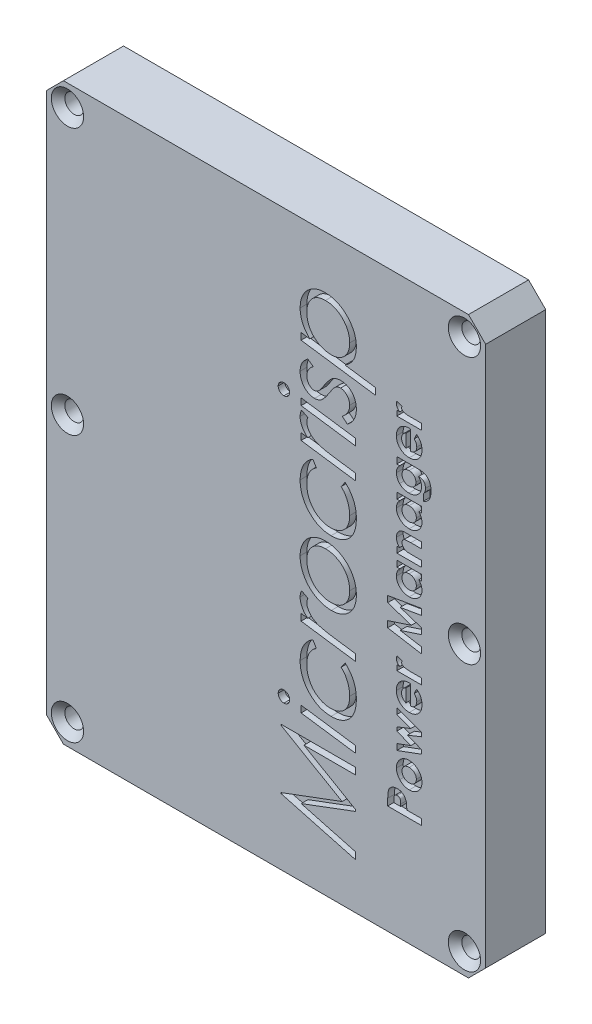
SolidWorks part; units mm, degrees
ref_plane "Front Plane" through (0, 0, 0) normal (0, 0, 1) x (1, 0, 0)
ref_plane "Top Plane" through (0, 0, 0) normal (0, 1, 0) x (1, 0, 0)
ref_plane "Right Plane" through (0, 0, 0) normal (1, 0, 0) x (0, 0, -1)
sketch "Sketch1" plane through (0, 0, 0) normal (0, 0, 1) x (1, 0, 0)
  line L0 (-27.5, 37.5) -> (27.5, 37.5) construction
  line L1 (27.5, 37.5) -> (27.5, -37.5) construction
  line L2 (27.5, -37.5) -> (-27.5, -37.5) construction
  line L3 (-27.5, -37.5) -> (-27.5, 37.5) construction
  line L4 (-27.5, 37.5) -> (27.5, 37.5)
  line L5 (27.5, 37.5) -> (27.5, -37.5)
  line L6 (27.5, -37.5) -> (-27.5, -37.5)
  line L7 (-27.5, -37.5) -> (-27.5, 37.5)
  line L8 (29.96, 42.5) -> (-29.96, 42.5)
  line L9 (-29.96, 42.5) -> (-32.5, 39.96)
  line L10 (-32.5, 39.96) -> (-32.5, -39.96)
  line L11 (-32.5, -39.96) -> (-29.96, -42.5)
  line L12 (-29.96, -42.5) -> (29.96, -42.5)
  line L13 (29.96, -42.5) -> (32.5, -39.96)
  line L14 (32.5, -39.96) -> (32.5, 39.96)
  line L15 (32.5, 39.96) -> (29.96, 42.5)
  line L16 (29.96, 42.5) -> (-29.96, 42.5)
  line L17 (-29.96, 42.5) -> (-32.5, 39.96)
  line L18 (-32.5, 39.96) -> (-32.5, -39.96)
  line L19 (-32.5, -39.96) -> (-29.96, -42.5)
  line L20 (-29.96, -42.5) -> (29.96, -42.5)
  line L21 (29.96, -42.5) -> (32.5, -39.96)
  line L22 (32.5, -39.96) -> (32.5, 39.96)
  line L23 (32.5, 39.96) -> (29.96, 42.5)
  circle A0 centre (29.365, 0) radius 0.889 construction
  circle A1 centre (29.365, -39.365) radius 0.889 construction
  circle A2 centre (29.365, 39.365) radius 0.889 construction
  circle A3 centre (-29.365, 39.365) radius 0.889 construction
  circle A4 centre (-29.365, -39.365) radius 0.889 construction
  circle A5 centre (-29.365, 0) radius 0.889 construction
  circle A24 centre (29.365, 0) radius 0.889 construction
  circle A25 centre (29.365, -39.365) radius 0.889 construction
  circle A26 centre (29.365, 39.365) radius 0.889 construction
  circle A27 centre (-29.365, 39.365) radius 0.889 construction
  circle A28 centre (-29.365, -39.365) radius 0.889 construction
  circle A29 centre (-29.365, 0) radius 0.889 construction
  circle A30 centre (29.365, 0) radius 1.389
  circle A31 centre (29.365, -39.365) radius 1.389
  circle A32 centre (29.365, 39.365) radius 1.389
  circle A33 centre (-29.365, 39.365) radius 1.389
  circle A34 centre (-29.365, -39.365) radius 1.389
  circle A35 centre (-29.365, 0) radius 1.389
  dimension "D1" = 0
  dimension "D2" = 0.5
extrude "Boss-Extrude1" add sketch "Sketch1" along normal offset from surface (8.89 mm away) 40.64
sketch "Sketch2" plane through (0, 0, 8.89) normal (0, 0, 1) x (1, 0, 0)
  line L0 (27.5, -37.5) -> (-27.5, -37.5) construction
  line L1 (27.5, 37.5) -> (27.5, -37.5) construction
  line L2 (-27.5, -37.5) -> (-27.5, 37.5) construction
  line L3 (-27.5, 37.5) -> (27.5, 37.5) construction
  line L4 (27.5, -37.5) -> (-27.5, -37.5)
  line L5 (27.5, 37.5) -> (27.5, -37.5)
  line L6 (-27.5, -37.5) -> (-27.5, 37.5)
  line L7 (-27.5, 37.5) -> (27.5, 37.5)
extrude "Boss-Extrude2" add sketch "Sketch2" against normal blind 4
chamfer "Chamfer1" distance 1 angle 45 6 edges at (27.976, 39.365, 8.89) (27.976, 0, 8.89) (27.976, -39.365, 8.89) (-30.754, -39.365, 8.89) (-30.754, 0, 8.89) (-30.754, 39.365, 8.89)
sketch "Sketch3" plane through (0, 0, 8.89) normal (0, 0, 1) x (1, 0, 0)
  line L0 (13.2344, -42.5) -> (13.2344, 42.5) construction
  line L1 (29.96, -42.5) -> (-29.96, -42.5) construction
  line L2 (-29.96, 42.5) -> (29.96, 42.5) construction
  line L3 (23.015, -42.5) -> (23.015, 42.5) construction
  text T0 "<i>Microcrisp</i>" font "Century Gothic" height 11
  text T1 "<b>Power Manager</b>" font "Century Gothic" height 5
extrude "Cut-Extrude1" cut sketch "Sketch3" against normal blind 1
